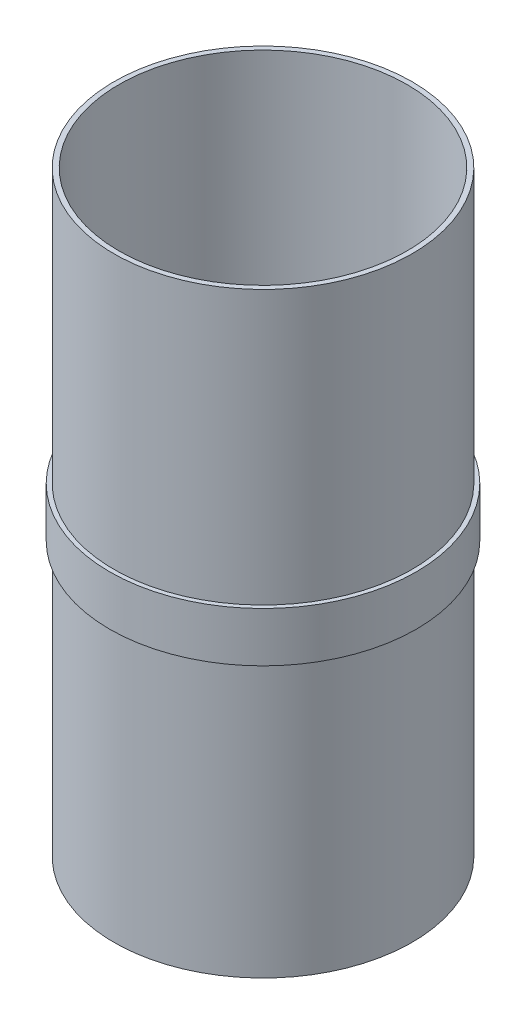
SolidWorks part; units mm, degrees
material "S-Glass Fiber"
ref_plane "Front Plane" through (0, 0, 0) normal (0, 0, 1) x (1, 0, 0)
ref_plane "Top Plane" through (0, 0, 0) normal (0, 1, 0) x (1, 0, 0)
ref_plane "Right Plane" through (0, 0, 0) normal (1, 0, 0) x (0, 0, -1)
sketch "Sketch1" plane through (0, 0, 0) normal (0, 1, 0) x (1, 0, 0)
  circle A0 centre (0, 0) radius 78.359
  circle A1 centre (0, 0) radius 76.2
  dimension "D1" = 152.4
  dimension "D2" = 156.718
extrude "Boss-Extrude1" add sketch "Sketch1" along normal mid plane 25.4
sketch "Sketch2" plane through (0, 0, 0) normal (0, 1, 0) x (1, 0, 0)
  circle A0 centre (0, 0) radius 76.2
  circle A1 centre (0, 0) radius 73.66
  dimension "D1" = 152.4
  dimension "D2" = 147.32
extrude "Boss-Extrude2" add sketch "Sketch2" along normal mid plane 304.8
